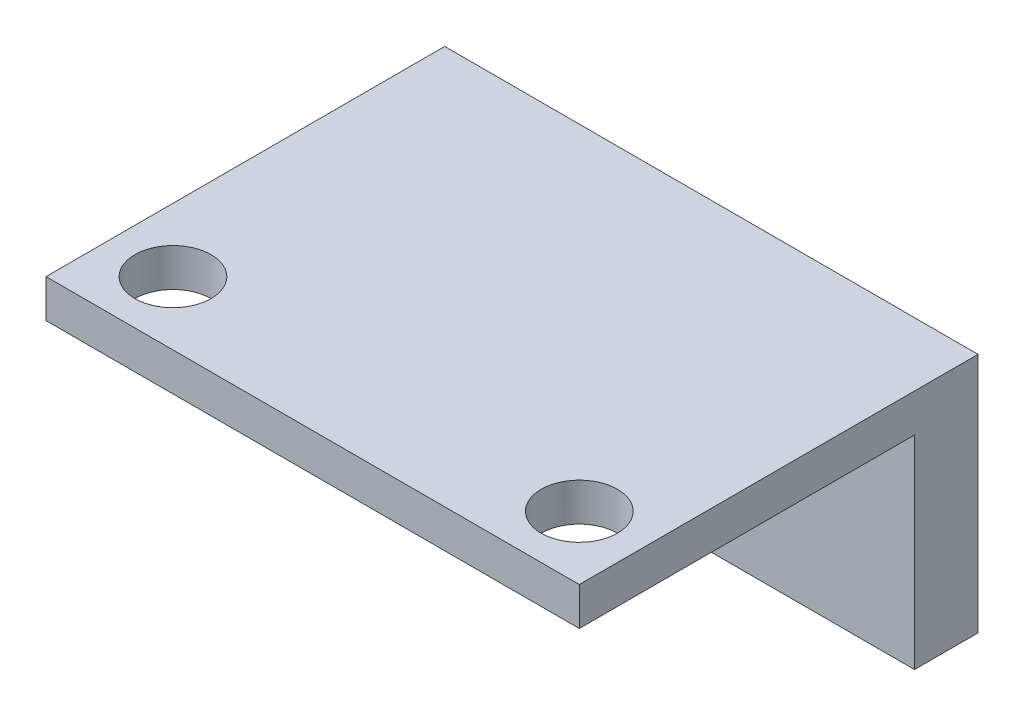
SolidWorks part; units mm, degrees
ref_plane "Front Plane" through (0, 0, 0) normal (0, 0, 1) x (1, 0, 0)
ref_plane "Top Plane" through (0, 0, 0) normal (0, 1, 0) x (1, 0, 0)
ref_plane "Right Plane" through (0, 0, 0) normal (1, 0, 0) x (0, 0, -1)
sketch "Sketch1" plane through (0, 0, 0) normal (0, 1, 0) x (1, 0, 0)
  line L1 (0, 0) -> (21, 0)
  line L2 (0, 0) -> (0, 15.7)
  line L3 (0, 15.7) -> (21, 15.7)
  line L4 (21, 0) -> (21, 15.7)
  dimension "D1" = 21
  dimension "D2" = 15.7
extrude "Boss-Extrude1" add sketch "Sketch1" along normal blind 1.5
sketch "Sketch2" plane through (0, 1.5, 0) normal (0, 1, 0) x (1, 0, 0)
  line L0 (0, 0) -> (21, 0) construction
  line L1 (0, 15.7) -> (0, 0) construction
  line L2 (21, 0) -> (21, 15.7) construction
  circle A0 centre (2.5, 2.5) radius 1.5
  circle A1 centre (18.5, 2.5) radius 1.5
  point P4 (0, 0)
  point P13 (20.5217, 0.5657)
  dimension "D1" = 3
  dimension "D2" = 2.5
  dimension "D3" = 2.5
  dimension "D4" = 2.5
extrude "Cut-Extrude1" cut sketch "Sketch2" against normal up to surface (1.5 mm away) up to face at (10.5, 0, -7.85)
sketch "Sketch3" plane through (0, 0, 0) normal (0, -1, 0) x (1, 0, 0)
  line L0 (21, 0) -> (21, -15.7) construction
  line L1 (0, -15.7) -> (21, -15.7)
  line L2 (0, -15.7) -> (0, -13.2)
  line L3 (0, -13.2) -> (21, -13.2)
  line L4 (21, -15.7) -> (21, -13.2)
  dimension "D1" = 2.5
extrude "Boss-Extrude2" add sketch "Sketch3" along normal blind 8
